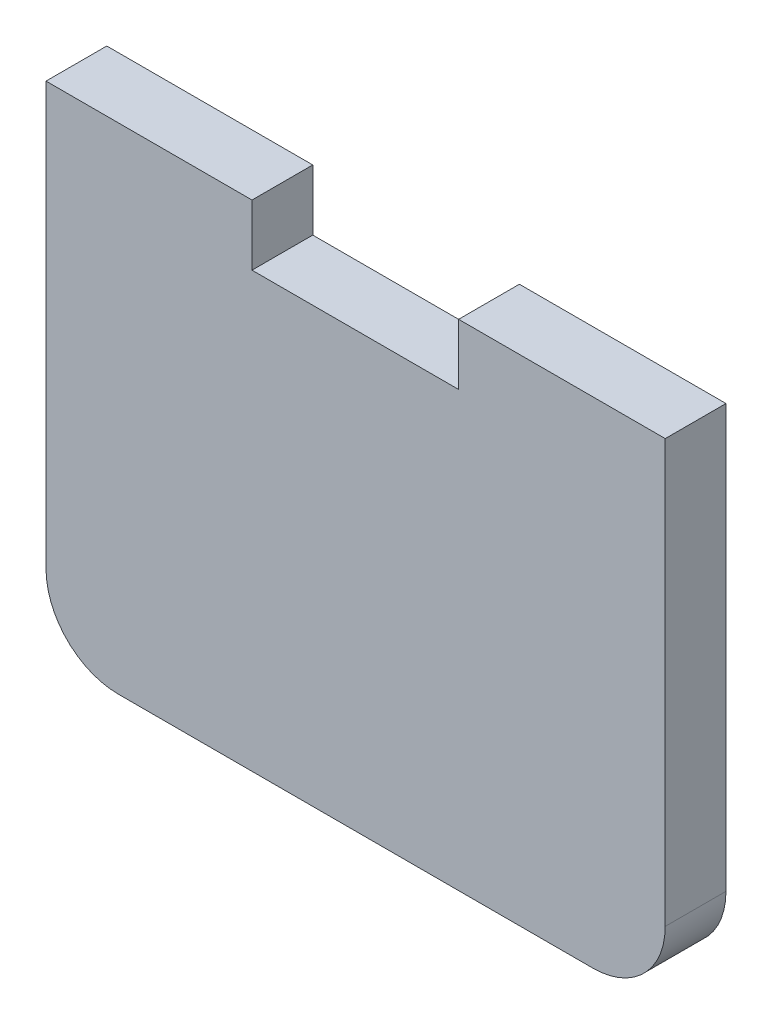
SolidWorks part; units mm, degrees
material "Teak"
ref_plane "Front Plane" through (0, 0, 0) normal (0, 0, 1) x (1, 0, 0)
ref_plane "Top Plane" through (0, 0, 0) normal (0, 1, 0) x (1, 0, 0)
ref_plane "Right Plane" through (0, 0, 0) normal (1, 0, 0) x (0, 0, -1)
sketch "Sketch1" plane through (0, 0, 0) normal (0, 0, 1) x (1, 0, 0)
  line L1 (-30.5325, 25.3111) -> (23.8235, 25.3111)
  line L2 (-30.5325, 25.3111) -> (-30.5325, -18.1229)
  line L3 (-30.5325, -18.1229) -> (23.8235, -18.1229)
  line L4 (23.8235, 25.3111) -> (23.8235, -18.1229)
  dimension "D1" = 43.434
  dimension "D2" = 54.356
extrude "Boss-Extrude1" add sketch "Sketch1" along normal blind 5.334 contours L1 L4 L3 L2
sketch "Sketch2" plane through (0, 0, 5.334) normal (0, 0, 1) x (1, 0, 0)
  line L0 (-30.5325, 25.3111) -> (23.8235, 25.3111) construction
  line L1 (-12.4506, 25.3111) -> (5.6865, 25.3111)
  line L2 (-12.4506, 25.3111) -> (-12.4506, 19.9771)
  line L3 (-12.4506, 19.9771) -> (5.6865, 19.9771)
  line L4 (5.6865, 25.3111) -> (5.6865, 19.9771)
  line L5 (-12.4506, 19.9771) -> (-30.5325, 19.9771) construction
  line L6 (-30.5325, 25.3111) -> (-30.5325, -18.1229) construction
  line L7 (5.6865, 19.9771) -> (23.8235, 19.9771) construction
  line L8 (23.8235, 25.3111) -> (23.8235, -18.1229) construction
  dimension "D1" = 5.334
extrude "Cut-Extrude1" cut sketch "Sketch2" against normal through all
fillet "Fillet1" radius 6.35 2 edges at (-30.5325, -18.1229, 2.667) (23.8235, -18.1229, 2.667)
equation "\"MDF\"= .21in"
equation "\"Foamcore\"= .13in"
equation "\"Gmaterial\"= \"MDF\""
equation "\"D1@Sketch1\"=\"MDF\"+1.5"
equation "\"D1@Boss-Extrude1\"=\"MDF\""
equation "\"D1@Sketch2\"=\"MDF\""
